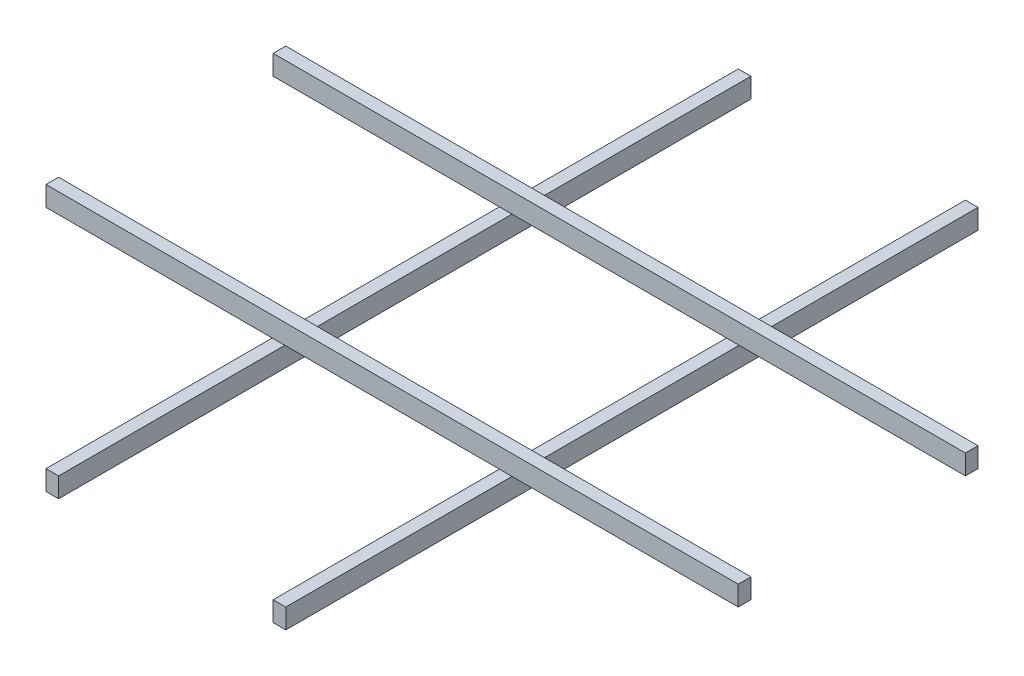
SolidWorks part; units mm, degrees
material "Doug Fir"
ref_plane "Front Plane" through (0, 0, 0) normal (0, 0, 1) x (1, 0, 0)
ref_plane "Top Plane" through (0, 0, 0) normal (0, 1, 0) x (1, 0, 0)
ref_plane "Right Plane" through (0, 0, 0) normal (1, 0, 0) x (0, 0, -1)
sketch "Lower Level" plane through (0, 0, 0) normal (0, 1, 0) x (1, 0, 0)
  line L0 (1333.5, 0) -> (1333.5, 4876.8)
  line L1 (2933.7, 0) -> (2933.7, 4876.8)
  line L2 (1333.5, 2438.4) -> (2933.7, 2438.4) construction
  point P7 (2133.6, 2438.4)
  dimension "D1" = 4876.8
  dimension "D2" = 800.1
ref_plane "Plane2" through (0, 139.7, 0) normal (0, 1, 0) x (1, 0, 0)
sketch "Sketch12" plane through (0, 139.7, 0) normal (0, 1, 0) x (1, 0, 0)
  line L0 (-304.8, 3238.5) -> (4572, 3238.5)
  line L1 (4572, 1638.3) -> (-304.8, 1638.3)
  line L2 (2133.6, 3238.5) -> (2133.6, 1638.3) construction
  point P0 (2133.6, 2438.4)
  point P6 (2133.6, 1638.3)
  point P7 (2133.6, 3238.5)
  point P10 (2133.6, 2438.4)
  dimension "D1" = 4876.8
  dimension "D2" = 800.1
other "Profiles 4X6(1)"
ref_plane "Plane1" through (1333.5, 0, 0) normal (0, 0, -1) x (-1, 0, 0)
sketch "Sketch1" plane through (1333.5, 0, 0) normal (0, 0, -1) x (-1, 0, 0)
  line L1 (-44.45, 69.85) -> (44.45, 69.85)
  line L2 (-44.45, 69.85) -> (-44.45, -69.85)
  line L3 (-44.45, -69.85) -> (44.45, -69.85)
  line L4 (44.45, 69.85) -> (44.45, -69.85)
  line L5 (-44.45, 69.85) -> (44.45, -69.85) construction
  line L6 (-44.45, -69.85) -> (44.45, 69.85) construction
  point P0 (0, 0)
  point P6 (0, 69.85)
  point P7 (0, -69.85)
  point P8 (44.45, 0)
  point P9 (-44.45, 0)
  point P10 (0, 0)
  dimension "D1" = 88.9
  dimension "D2" = 139.7
sketch3d "3DSketch2"
  line L0 (2133.6, 139.7, -2438.4) -> (2133.6, 0, -2438.4)
  line L1 (1333.5, 0, -2438.4) -> (2933.7, 0, -2438.4) construction
equation "\"Width\" = 31.5"
equation "\"Length\"=192"
equation "\"D1@Lower Level\"=\"Length\""
equation "\"D2@Lower Level\"=\"Width\""
equation "\"D1@Sketch12\"=\"Length\""
equation "\"D2@Sketch12\"=\"Width\""
